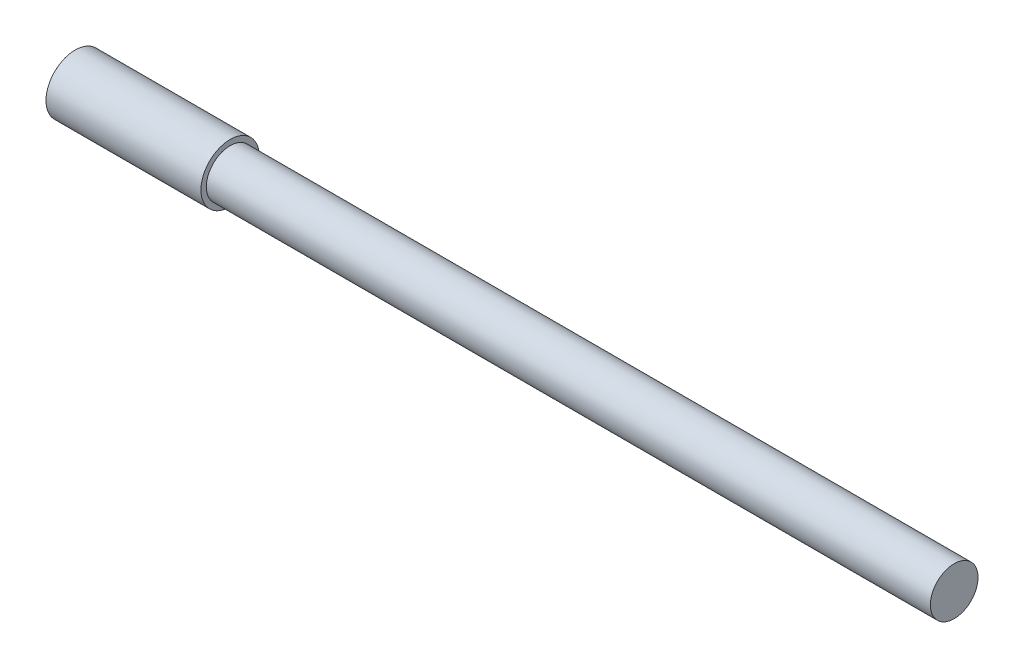
SolidWorks part; units mm, degrees
ref_plane "Front Plane" through (0, 0, 0) normal (0, 0, 1) x (1, 0, 0)
ref_plane "Top Plane" through (0, 0, 0) normal (0, 1, 0) x (1, 0, 0)
ref_plane "Right Plane" through (0, 0, 0) normal (1, 0, 0) x (0, 0, -1)
sketch "Sketch1" plane through (0, 0, 0) normal (0, 1, 0) x (1, 0, 0)
  line L0 (0, 0) -> (26, 0)
  line L1 (26, 0) -> (26, 0.9)
  line L2 (26, 0.9) -> (147.5, 0.9)
  line L8 (0, 0) -> (0, 4.9)
  line L9 (0, 4.9) -> (206.9028, 4.9) construction
  line L10 (147.5, 0.9) -> (147.5, 4.9)
  line L11 (147.5, 4.9) -> (0, 4.9)
  dimension "D1" = 0.9
  dimension "D2" = 4
  dimension "D6" = 4.9
revolve "Revolve1" add sketch "Sketch1" angle 360 about L9
